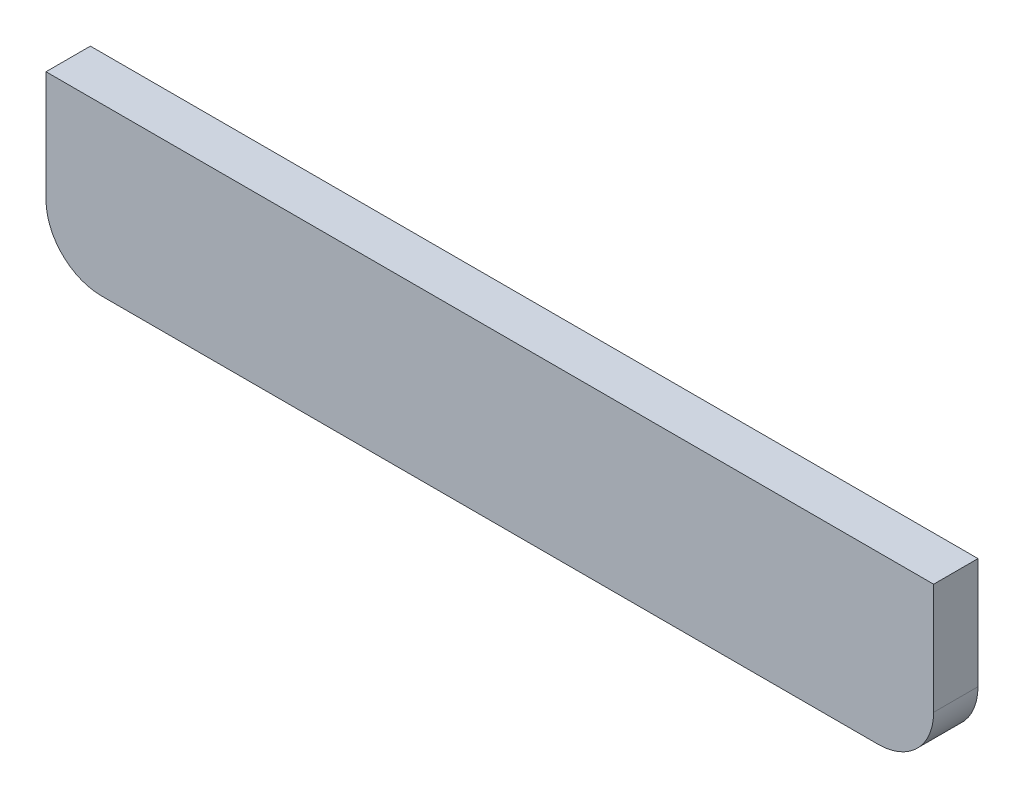
SolidWorks part; units mm, degrees
ref_plane "Front Plane" through (0, 0, 0) normal (0, 0, 1) x (1, 0, 0)
ref_plane "Top Plane" through (0, 0, 0) normal (0, 1, 0) x (1, 0, 0)
ref_plane "Right Plane" through (0, 0, 0) normal (1, 0, 0) x (0, 0, -1)
sketch "Sketch1" plane through (0, 0, 0) normal (0, 0, 1) x (1, 0, 0)
  line L1 (80, -15) -> (-80, -15)
  line L2 (80, -15) -> (80, 15)
  line L3 (80, 15) -> (-80, 15)
  line L4 (-80, -15) -> (-80, 15)
  line L5 (80, -15) -> (-80, 15) construction
  line L6 (80, 15) -> (-80, -15) construction
  point P0 (0, 0)
  dimension "D1" = 30
  dimension "D2" = 160
extrude "Boss-Extrude1" add sketch "Sketch1" along normal mid plane 8
fillet "Fillet1" radius 10 2 edges at (80, -15, 0) (-80, -15, 0)
